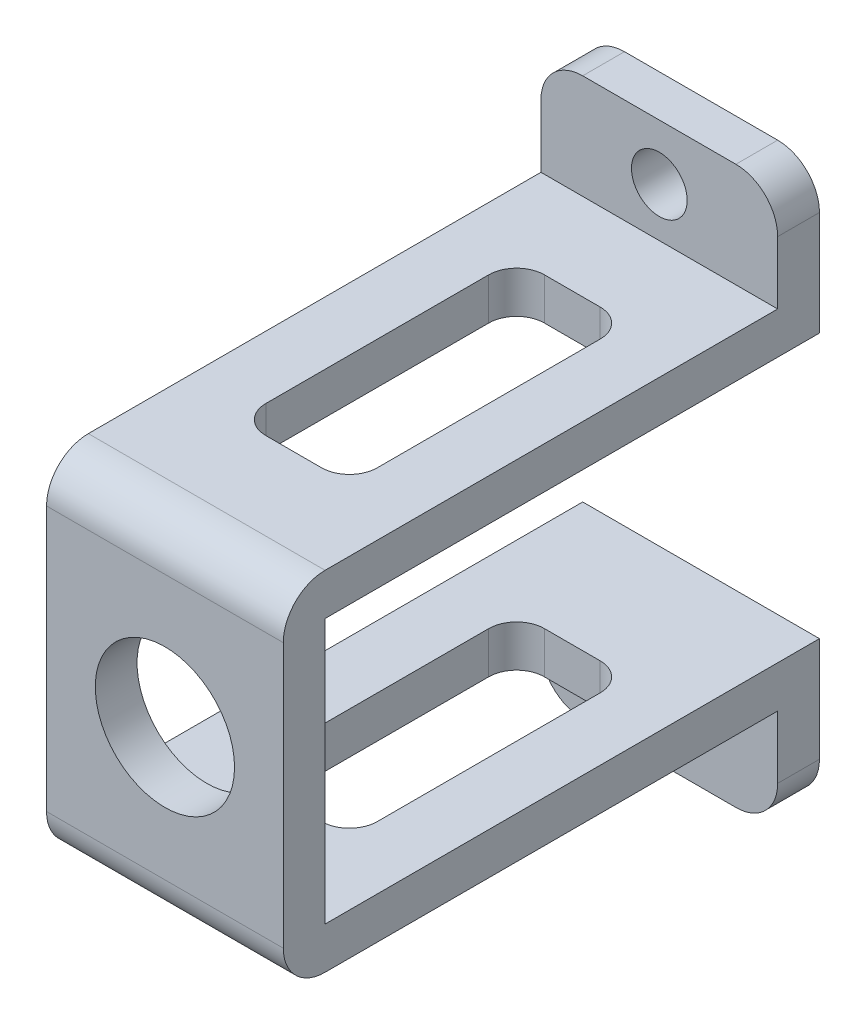
SolidWorks part; units mm, degrees
material "6061 合金"
ref_plane "前视基准面" through (0, 0, 0) normal (0, 0, 1) x (1, 0, 0)
ref_plane "上视基准面" through (0, 0, 0) normal (0, 1, 0) x (1, 0, 0)
ref_plane "右视基准面" through (0, 0, 0) normal (1, 0, 0) x (0, 0, -1)
sketch "草图1" plane through (0, 0, 0) normal (0, 0, 1) x (1, 0, 0)
  line L1 (-4, -10) -> (4, -10)
  line L2 (-4, -10) -> (-4, 10)
  line L3 (-4, 10) -> (4, 10)
  line L4 (4, -10) -> (4, 10)
  line L5 (-4, -10) -> (4, 10) construction
  line L6 (-4, 10) -> (4, -10) construction
  circle A0 centre (0, 0) radius 2
  circle A1 centre (0, 0) radius 7.5
  dimension "D1" = 20
  dimension "D2" = 8
extrude "凸台-拉伸1" add sketch "草图1" along normal blind 2 contours L4 A1 | L4 A1 L2 A0 | L2 A1 | A1 L4 L3 L2 | A1 L2 L1 L4
sketch "草图4" plane through (0, 0, 2) normal (0, 0, 1) x (1, 0, 0)
  line L5 (-4, -10) -> (4, -10)
  line L6 (-4, -10) -> (-4, -12)
  line L7 (-4, -12) -> (4, -12)
  line L8 (4, -10) -> (4, -12)
  line L9 (-4, 10) -> (4, 10)
  line L10 (-4, 10) -> (-4, 12)
  line L11 (-4, 12) -> (4, 12)
  line L12 (4, 10) -> (4, 12)
  dimension "D1" = 2
  dimension "D2" = 8
  dimension "D3" = 2
  dimension "D4" = 8
extrude "凸台-拉伸3" add sketch "草图4" against normal blind 35.5
sketch "草图5" plane through (0, 0, 0) normal (0, 0, -1) x (-1, 0, 0)
  circle A0 centre (0, 0) radius 5.5 construction
  circle A1 centre (0, 5.5) radius 1
  circle A2 centre (0, -5.5) radius 1
extrude "切除-拉伸1" cut sketch "草图5" against normal blind 8
sketch "草图6" plane through (0, 0, -33.5) normal (0, 0, -1) x (-1, 0, 0)
  line L5 (-4, -10) -> (4, -10)
  line L6 (-4, -10) -> (-4, -20)
  line L7 (-4, -20) -> (4, -20)
  line L8 (4, -10) -> (4, -20)
  line L9 (-4, 10) -> (4, 10)
  line L10 (-4, 10) -> (-4, 20)
  line L11 (-4, 20) -> (4, 20)
  line L12 (4, 10) -> (4, 20)
  dimension "D1" = 10
  dimension "D2" = 8
  dimension "D3" = 10
  dimension "D4" = 8
extrude "凸台-拉伸4" add sketch "草图6" along normal blind 2
sketch "草图7" plane through (0, 0, -33.5) normal (0, 0, 1) x (1, 0, 0)
  circle A0 centre (0, 0) radius 16 construction
  circle A1 centre (0, 16) radius 2
  circle A2 centre (0, -16) radius 2
extrude "切除-拉伸2" cut sketch "草图7" against normal blind 2
sketch "草图8" plane through (-4, 0, 0) normal (-1, 0, 0) x (0, 0, 1)
  line L0 (0, 6.3443) -> (0, -6.3443) construction
  line L1 (2, -6.3443) -> (2, 6.3443) construction
  line L2 (0, 6.3443) -> (0, -6.3443)
  line L3 (2, -6.3443) -> (2, 6.3443)
  line L4 (0, 6.3443) -> (0, -6.3443)
  line L5 (0, -6.3443) -> (2, -6.3443)
  line L6 (2, -6.3443) -> (2, 6.3443)
  line L7 (2, 6.3443) -> (0, 6.3443)
  line L8 (0, 10) -> (0, 6.3443)
  line L9 (0, 6.3443) -> (2, 6.3443)
  line L10 (2, 6.3443) -> (2, 12)
  line L11 (2, 12) -> (-33.5, 12)
  line L12 (-33.5, 12) -> (-33.5, 20)
  line L13 (-33.5, 20) -> (-35.5, 20)
  line L14 (-35.5, 20) -> (-35.5, 10)
  line L15 (-35.5, 10) -> (0, 10)
  line L16 (0, 10) -> (0, 6.3443)
  line L18 (2, 6.3443) -> (2, 12)
  line L19 (2, 12) -> (-33.5, 12)
  line L20 (-33.5, 12) -> (-33.5, 20)
  line L21 (-33.5, 20) -> (-35.5, 20)
  line L22 (-35.5, 20) -> (-35.5, 10)
  line L23 (-35.5, 10) -> (0, 10)
  line L24 (0, -6.3443) -> (0, -10)
  line L25 (0, -10) -> (-35.5, -10)
  line L26 (-35.5, -10) -> (-35.5, -20)
  line L27 (-35.5, -20) -> (-33.5, -20)
  line L28 (-33.5, -20) -> (-33.5, -12)
  line L29 (-33.5, -12) -> (2, -12)
  line L30 (2, -12) -> (2, -6.3443)
  line L31 (2, -6.3443) -> (0, -6.3443)
  line L32 (0, -6.3443) -> (0, -10)
  line L33 (0, -10) -> (-35.5, -10)
  line L34 (-35.5, -10) -> (-35.5, -20)
  line L35 (-35.5, -20) -> (-33.5, -20)
  line L36 (-33.5, -20) -> (-33.5, -12)
  line L37 (-33.5, -12) -> (2, -12)
  line L38 (2, -12) -> (2, -6.3443)
  line L40 (0, 6.3443) -> (0, -6.3443)
  line L42 (2, -6.3443) -> (2, 6.3443)
  line M21 (0, 10) -> (0, 6.3443)
  line M22 (0, 6.3443) -> (2, 6.3443)
  line M23 (2, 6.3443) -> (2, 12)
  line M24 (2, 12) -> (-33.5, 12)
  line M25 (-33.5, 12) -> (-33.5, 20)
  line M26 (-33.5, 20) -> (-35.5, 20)
  line M27 (-35.5, 20) -> (-35.5, 10)
  line M28 (-35.5, 10) -> (0, 10)
  dimension "D1" = 0
  dimension "D2" = 0
  dimension "D3" = 0
extrude "凸台-拉伸5" add sketch "草图8" along normal blind 4.5 contours M28 M21 M22 M23 M24 M25 M26 M27 | L37 L38 L3 L2 L32 L33 L34 L35 L36 M22
sketch "草图9" plane through (4, 0, 0) normal (1, 0, 0) x (0, 0, -1)
  line L0 (-2, 6.3443) -> (-2, -6.3443) construction
  line L1 (0, -6.3443) -> (0, 6.3443) construction
  line L2 (-2, 6.3443) -> (-2, -6.3443)
  line L3 (0, -6.3443) -> (0, 6.3443)
  line L8 (0, 6.3443) -> (0, 10)
  line L9 (0, 10) -> (35.5, 10)
  line L10 (35.5, 10) -> (35.5, 20)
  line L11 (35.5, 20) -> (33.5, 20)
  line L12 (33.5, 20) -> (33.5, 12)
  line L13 (33.5, 12) -> (-2, 12)
  line L14 (-2, 12) -> (-2, 6.3443)
  line L15 (-2, 6.3443) -> (0, 6.3443)
  line L16 (0, 6.3443) -> (0, 10)
  line L17 (0, 10) -> (35.5, 10)
  line L18 (35.5, 10) -> (35.5, 20)
  line L19 (35.5, 20) -> (33.5, 20)
  line L20 (33.5, 20) -> (33.5, 12)
  line L21 (33.5, 12) -> (-2, 12)
  line L22 (-2, 12) -> (-2, 6.3443)
  line L24 (0, -10) -> (0, -6.3443)
  line L25 (0, -6.3443) -> (-2, -6.3443)
  line L26 (-2, -6.3443) -> (-2, -12)
  line L27 (-2, -12) -> (33.5, -12)
  line L28 (33.5, -12) -> (33.5, -20)
  line L29 (33.5, -20) -> (35.5, -20)
  line L30 (35.5, -20) -> (35.5, -10)
  line L31 (35.5, -10) -> (0, -10)
  line L32 (0, -10) -> (0, -6.3443)
  line L34 (-2, -6.3443) -> (-2, -12)
  line L35 (-2, -12) -> (33.5, -12)
  line L36 (33.5, -12) -> (33.5, -20)
  line L37 (33.5, -20) -> (35.5, -20)
  line L38 (35.5, -20) -> (35.5, -10)
  line L39 (35.5, -10) -> (0, -10)
  dimension "D1" = 0
  dimension "D2" = 0
extrude "凸台-拉伸6" add sketch "草图9" along normal blind 4.5
fillet "圆角1" radius 3 4 edges at (-8.5, -20, -34.5) (8.5, -20, -34.5) (-8.5, 20, -34.5) (8.5, 20, -34.5)
sketch "草图10" plane through (0, 0, 2) normal (0, 0, 1) x (1, 0, 0)
  line L4 (8.5, -12) -> (8.5, 12)
  line L5 (8.5, 12) -> (-8.5, 12)
  line L6 (-8.5, 12) -> (-8.5, -12)
  line L7 (-8.5, -12) -> (8.5, -12)
  line L8 (8.5, -12) -> (8.5, 12)
  line L9 (8.5, 12) -> (-8.5, 12)
  line L10 (-8.5, 12) -> (-8.5, -12)
  line L11 (-8.5, -12) -> (8.5, -12)
  circle A0 centre (0, -5.5) radius 1 construction
  circle A1 centre (0, 0) radius 2 construction
  circle A2 centre (0, 5.5) radius 1 construction
  circle A3 centre (0, -5.5) radius 1
  circle A4 centre (0, 0) radius 2
  circle A5 centre (0, 5.5) radius 1
  dimension "D1" = 0
extrude "凸台-拉伸7" add sketch "草图10" along normal blind 1
sketch "草图12" plane through (0, 10, 0) normal (0, -1, 0) x (1, 0, 0)
  line L4 (8.5, 0) -> (-8.5, 0)
  line L5 (-8.5, 0) -> (-8.5, -35.5)
  line L6 (-8.5, -35.5) -> (8.5, -35.5)
  line L7 (8.5, -35.5) -> (8.5, 0)
  line L8 (8.5, 0) -> (-8.5, 0)
  line L9 (-8.5, 0) -> (-8.5, -35.5)
  line L10 (-8.5, -35.5) -> (8.5, -35.5)
  line L11 (8.5, -35.5) -> (8.5, 0)
  dimension "D1" = 0
extrude "凸台-拉伸8" add sketch "草图12" along normal blind 0.5
sketch "草图13" plane through (0, -10, 0) normal (0, 1, 0) x (1, 0, 0)
  line L4 (8.5, 35.5) -> (-8.5, 35.5)
  line L5 (-8.5, 35.5) -> (-8.5, 0)
  line L6 (-8.5, 0) -> (8.5, 0)
  line L7 (8.5, 0) -> (8.5, 35.5)
  line L8 (8.5, 35.5) -> (-8.5, 35.5)
  line L9 (-8.5, 35.5) -> (-8.5, 0)
  line L10 (-8.5, 0) -> (8.5, 0)
  line L11 (8.5, 0) -> (8.5, 35.5)
  dimension "D1" = 0
extrude "凸台-拉伸9" add sketch "草图13" along normal blind 0.5
sketch "草图14" plane through (0, 0, -33.5) normal (0, 0, 1) x (1, 0, 0)
  line L4 (-8.5, -12) -> (-8.5, -17)
  line L5 (-5.5, -20) -> (5.5, -20)
  line L6 (8.5, -17) -> (8.5, -12)
  line L7 (8.5, -12) -> (-8.5, -12)
  line L8 (-8.5, -12) -> (-8.5, -17)
  line L9 (-5.5, -20) -> (5.5, -20)
  line L10 (8.5, -17) -> (8.5, -12)
  line L11 (8.5, -12) -> (-8.5, -12)
  line L12 (5.5, 20) -> (-5.5, 20)
  line L13 (-8.5, 17) -> (-8.5, 12)
  line L14 (-8.5, 12) -> (8.5, 12)
  line L15 (8.5, 12) -> (8.5, 17)
  line L16 (5.5, 20) -> (-5.5, 20)
  line L17 (-8.5, 17) -> (-8.5, 12)
  line L18 (-8.5, 12) -> (8.5, 12)
  line L19 (8.5, 12) -> (8.5, 17)
  circle A0 centre (0, -16) radius 2 construction
  circle A1 centre (0, 16) radius 2 construction
  arc A2 (-8.5, -17) -> (-5.5, -20) centre (-5.5, -17) ccw
  arc A3 (5.5, -20) -> (8.5, -17) centre (5.5, -17) ccw
  arc A4 (-8.5, -17) -> (-5.5, -20) centre (-5.5, -17) ccw
  arc A5 (5.5, -20) -> (8.5, -17) centre (5.5, -17) ccw
  arc A6 (-5.5, 20) -> (-8.5, 17) centre (-5.5, 17) ccw
  arc A7 (8.5, 17) -> (5.5, 20) centre (5.5, 17) ccw
  arc A8 (-5.5, 20) -> (-8.5, 17) centre (-5.5, 17) ccw
  arc A9 (8.5, 17) -> (5.5, 20) centre (5.5, 17) ccw
  circle A10 centre (0, -16) radius 2
  circle A11 centre (0, 16) radius 2
  dimension "D1" = 0
  dimension "D2" = 0
extrude "凸台-拉伸10" add sketch "草图14" along normal blind 1
sketch "草图16" plane through (0, -12, 0) normal (0, -1, 0) x (1, 0, 0)
  line L4 (-8.5, -32.5) -> (8.5, -32.5)
  line L5 (8.5, -32.5) -> (8.5, 3)
  line L6 (8.5, 3) -> (-8.5, 3)
  line L7 (-8.5, 3) -> (-8.5, -32.5)
  line L8 (-8.5, -32.5) -> (8.5, -32.5)
  line L9 (8.5, -32.5) -> (8.5, 3)
  line L10 (8.5, 3) -> (-8.5, 3)
  line L11 (-8.5, 3) -> (-8.5, -32.5)
  dimension "D1" = 0
extrude "凸台-拉伸11" add sketch "草图16" along normal blind 0.5
sketch "草图17" plane through (0, 12, 0) normal (0, 1, 0) x (1, 0, 0)
  line L4 (8.5, 32.5) -> (-8.5, 32.5)
  line L5 (-8.5, 32.5) -> (-8.5, -3)
  line L6 (-8.5, -3) -> (8.5, -3)
  line L7 (8.5, -3) -> (8.5, 32.5)
  line L8 (8.5, 32.5) -> (-8.5, 32.5)
  line L9 (-8.5, 32.5) -> (-8.5, -3)
  line L10 (-8.5, -3) -> (8.5, -3)
  line L11 (8.5, -3) -> (8.5, 32.5)
  dimension "D1" = 0
extrude "凸台-拉伸12" add sketch "草图17" along normal blind 0.5
sketch "草图18" plane through (0, 0, 3) normal (0, 0, 1) x (1, 0, 0)
  circle A0 centre (0, -5.5) radius 1 construction
  circle A1 centre (0, 5.5) radius 1 construction
  circle A2 centre (0, -5.5) radius 1
  circle A3 centre (0, 5.5) radius 1
extrude "凸台-拉伸13" add sketch "草图18" against normal blind 3
sketch "草图19" plane through (0, 0, 3) normal (0, 0, 1) x (1, 0, 0)
  circle A0 centre (0, 0) radius 5
  dimension "D1" = 10
extrude "切除-拉伸3" cut sketch "草图19" against normal blind 3
sketch "草图20" plane through (0, 12.5, 0) normal (0, 1, 0) x (1, 0, 0)
  line L0 (-8.5, 14.75) -> (8.5, 14.75) construction
  line L1 (-8.5, 32.5) -> (-8.5, -3) construction
  line L3 (0, 35.5) -> (0, 24.75) construction
  line L8 (-5.5, 35.5) -> (5.5, 35.5) construction
  line L9 (-8.5, -3) -> (8.5, -3) construction
  line L10 (0, 16.2498) -> (0, -3) construction
  line L11 (0, 16.2498) -> (0, -3) construction
  line L13 (-4, 6.2498) -> (4, 6.2498)
  line L14 (-4, 6.2498) -> (-4, 26.2498)
  line L15 (-4, 26.2498) -> (4, 26.2498)
  line L16 (4, 6.2498) -> (4, 26.2498)
  line L17 (-4, 6.2498) -> (4, 26.2498) construction
  line L18 (-4, 26.2498) -> (4, 6.2498) construction
  point P6 (0, 14.75)
  dimension "D1" = 20
  dimension "D2" = 8
extrude "切除-拉伸4" cut sketch "草图20" against normal blind 34
fillet "圆角3" radius 2 8 edges at (4, 11, -6.2498) (-4, 11, -6.2498) (-4, 11, -26.2498) (4, 11, -26.2498) (4, -11, -6.2498) (-4, -11, -6.2498) (4, -11, -26.2498) (-4, -11, -26.2498)
fillet "圆角4" radius 3 2 edges at (0, -12.5, 3) (0, 12.5, 3)
equation "\"35。5\"=25"
